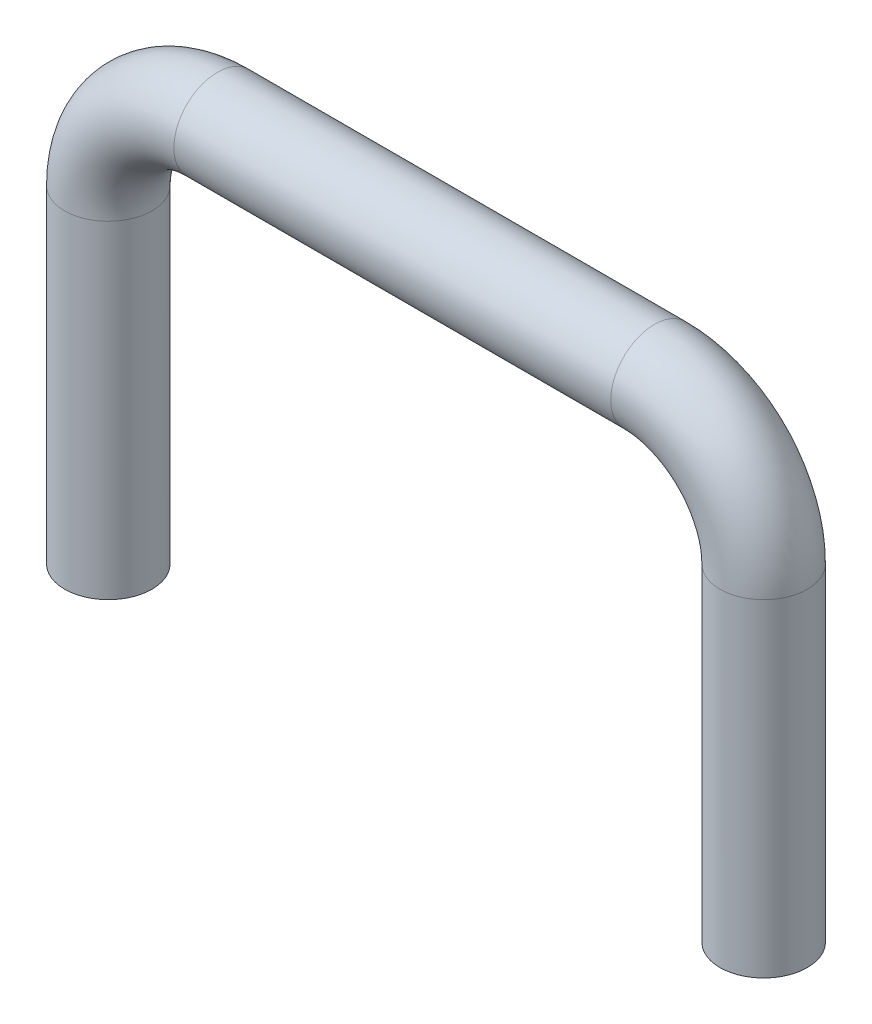
SolidWorks part; units mm, degrees
ref_plane "Alzado" through (0, 0, 0) normal (0, 0, 1) x (1, 0, 0)
ref_plane "Planta" through (0, 0, 0) normal (0, 1, 0) x (1, 0, 0)
ref_plane "Vista lateral" through (0, 0, 0) normal (1, 0, 0) x (0, 0, -1)
sketch "Croquis1" plane through (0, 0, 0) normal (0, 0, 1) x (1, 0, 0)
  line L0 (-15, 0) -> (-15, 15)
  line L1 (-10, 20) -> (10, 20)
  line L2 (15, 15) -> (15, 0)
  arc A0 (-15, 15) -> (-10, 20) centre (-10, 15) cw
  arc A1 (10, 20) -> (15, 15) centre (10, 15) cw
  point P7 (0, 20)
  point P8 (0, 0)
  point P11 (19.4996, 17.3137)
  point P12 (0, 0)
  point P13 (-17.7037, 12.7037)
  point P14 (0, 0)
  dimension "D3" = 5
  dimension "D1" = 20
  dimension "D2" = 30
sketch "Croquis2" plane through (0, 0, 0) normal (0, 1, 0) x (1, 0, 0)
  line L0 (-15, 0) -> (-10, 0) construction
  circle A0 centre (-15, 0) radius 2
  point P4 (0, 0)
  dimension "D1" = 4
sweep "Barrer1" add profiles "Croquis2" path "Croquis1"
